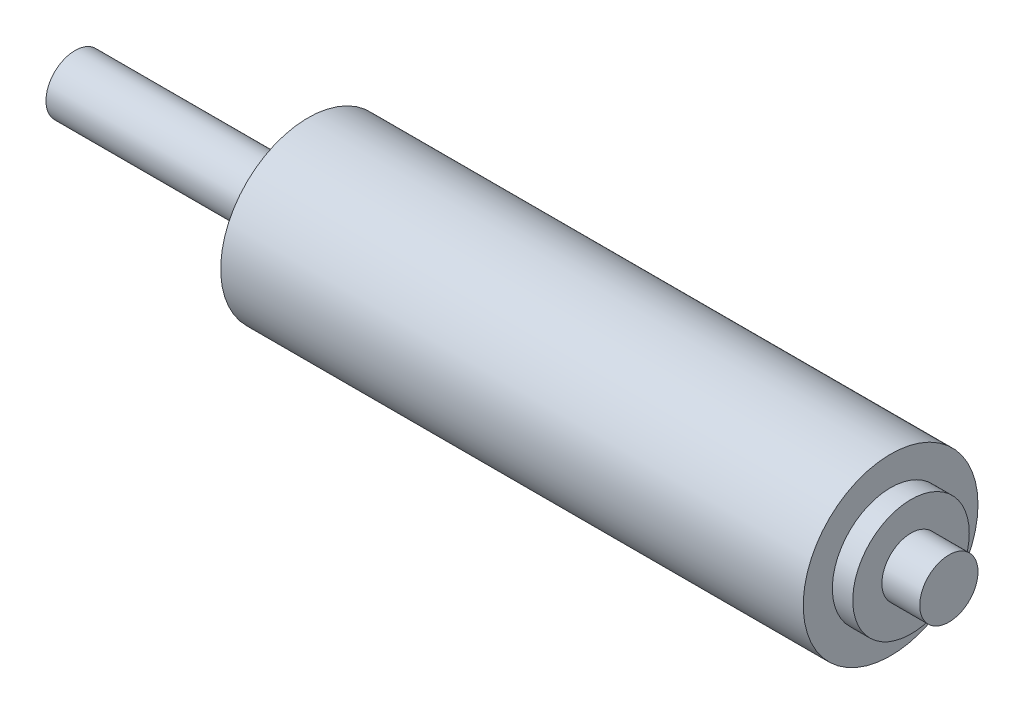
SolidWorks part; units mm, degrees
ref_plane "前视基准面" through (0, 0, 0) normal (0, 0, 1) x (1, 0, 0)
ref_plane "上视基准面" through (0, 0, 0) normal (0, 1, 0) x (1, 0, 0)
ref_plane "右视基准面" through (0, 0, 0) normal (1, 0, 0) x (0, 0, -1)
sketch "草图1" plane through (0, 0, 0) normal (0, 0, 1) x (1, 0, 0)
  line L0 (0, 0) -> (0, 5)
  line L1 (0, 5) -> (36.5, 5)
  line L3 (40, 15) -> (140, 15)
  line L4 (140, 15) -> (140, 10)
  line L6 (150, 5) -> (150, 0)
  line L7 (150, 0) -> (0, 0)
  line L8 (140, 10) -> (143.5, 10)
  line L9 (143.5, 10) -> (143.5, 5)
  line L10 (143.5, 5) -> (150, 5)
  line L11 (36.5, 5) -> (36.5, 10)
  line L12 (36.5, 10) -> (40, 10)
  line L13 (40, 10) -> (40, 15)
  point P3 (100, 10)
  point P11 (36.5, 5)
  dimension "D1" = 5
  dimension "D2" = 40
  dimension "D3" = 100
  dimension "D4" = 3.5
  dimension "D5" = 5
  dimension "D6" = 3.5
  dimension "D7" = 5
  dimension "D8" = 6.5
  dimension "D9" = 5
  dimension "D10" = 5
revolve "旋转1" add sketch "草图1" angle 360 about L7
